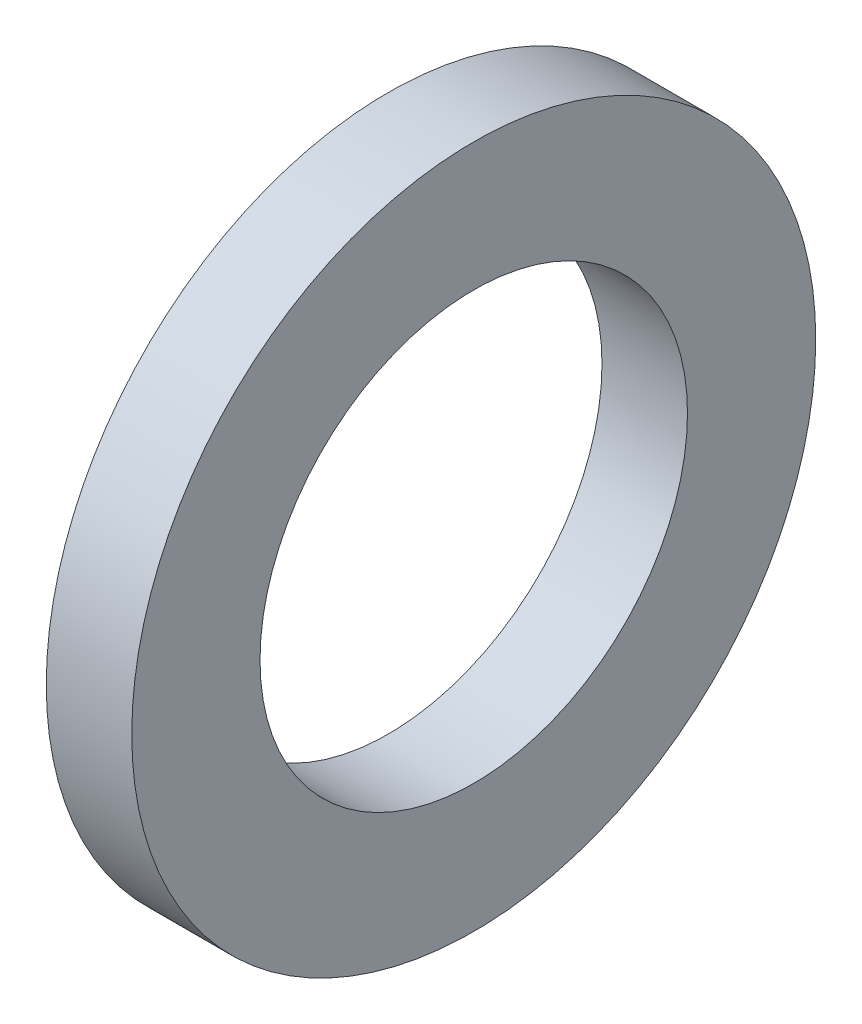
SolidWorks part; units mm, degrees
ref_plane "Front Plane" through (0, 0, 0) normal (0, 0, 1) x (1, 0, 0)
ref_plane "Top Plane" through (0, 0, 0) normal (0, 1, 0) x (1, 0, 0)
ref_plane "Right Plane" through (0, 0, 0) normal (1, 0, 0) x (0, 0, -1)
sketch "Sketch2" plane through (0, 0, 0) normal (1, 0, 0) x (0, 0, -1)
  circle A0 centre (0, 0) radius 6
  dimension "D1" = 12
extrude "Boss-Extrude1" add sketch "Sketch2" along normal mid plane 1.5
sketch "Sketch3" plane through (0.75, 0, 0) normal (1, 0, 0) x (0, 0, -1)
  circle A0 centre (0, 0) radius 3.75
  dimension "D1" = 7.5
extrude "Cut-Extrude1" cut sketch "Sketch3" against normal through all both and the other way through all
